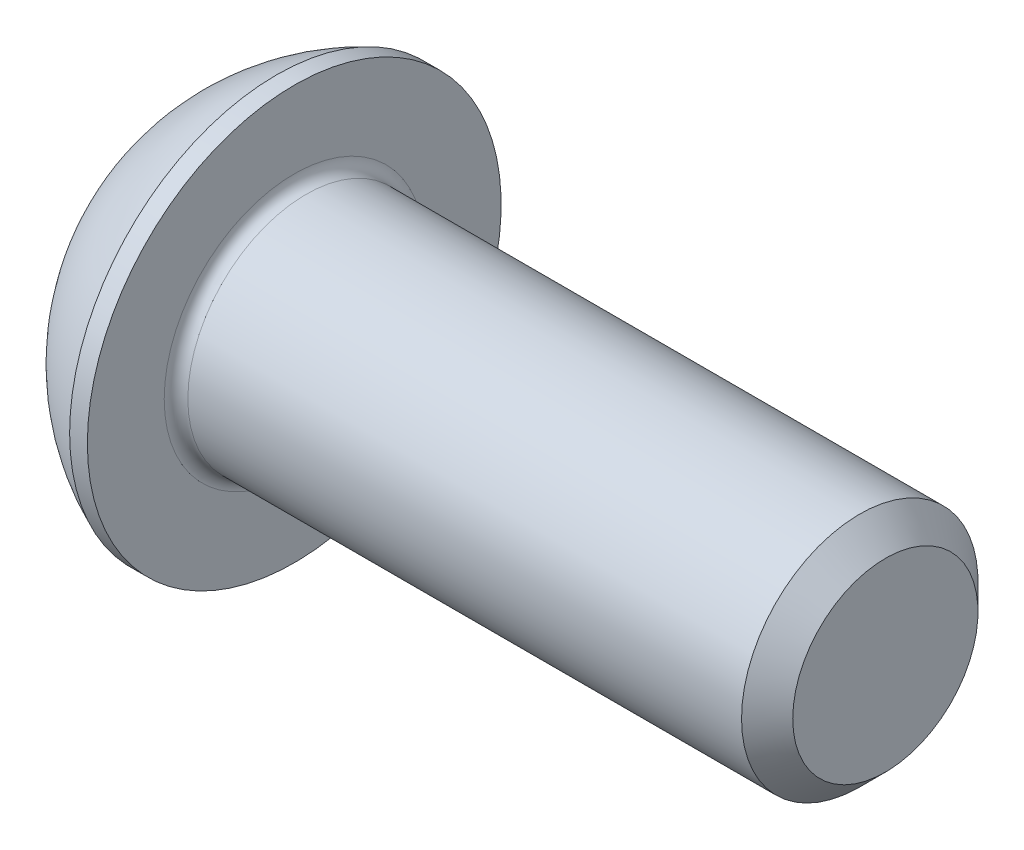
SolidWorks part; units mm, degrees
ref_plane "Plane1" through (0, 0, 0) normal (0, 0, 1) x (1, 0, 0)
ref_plane "Plane2" through (0, 0, 0) normal (0, 1, 0) x (1, 0, 0)
ref_plane "Plane3" through (0, 0, 0) normal (1, 0, 0) x (0, 0, -1)
sketch "BodySke" plane through (0, 0, 0) normal (0, 0, 1) x (1, 0, 0)
  line L0 (6.1, 0) -> (6.1, 0.7835)
  line L1 (5.8835, 1) -> (1.1, 1)
  line L2 (1.1, 1) -> (1.1, 1.75)
  line L3 (1.1, 1.75) -> (0.95, 1.75)
  line L4 (0, 0) -> (101.6, 0) construction
  line L5 (1.1, -1.75) -> (0.95, -1.75) construction
  line L6 (55.6768, -1) -> (1.1, -1) construction
  line L7 (6.1, 0) -> (0, 0)
  line L8 (0, 0.875) -> (0, -0.875) construction
  line L9 (0, 0) -> (0, 0.875)
  line L10 (6.1, 0.7835) -> (5.8835, 1)
  line L11 (6.1, -0.7835) -> (5.8835, -1) construction
  line L12 (1.5, 9.525) -> (1.5, -1) construction
  line L13 (1.1, 9.525) -> (1.1, -1) construction
  arc A1 (0, 0.875) -> (0.95, 1.75) centre (1.6839, 0) cw
  dimension "Diameter" = 2
  dimension "Length" = 5
  dimension "Head_dia" = 3.5
  dimension "D1" = 1.75
  dimension "Head_ht" = 1.1
  dimension "Head_side_ht" = 0.15
  dimension "Minor_dia" = 1.567
  dimension "Body_ch_ang" = 45
  dimension "Advance" = 0.4
  dimension "Thread_nom" = 5
revolve "BaseBody" add sketch "BodySke" angle 360 about L4
cosmetic thread "ThreadCosmetic" [suppressed] parameters "Thread_length"=4.2, "Thread_minor"=1.567
fillet "Fillet1" radius 0.1 1 edges at (1.1, 0, 1)
sketch "Sketch2" plane through (0, 0, 0) normal (0, 0, 1) x (1, 0, 0)
  line L0 (0, 0.715) -> (0.605, 0.715)
  line L1 (0.605, 0.715) -> (1.0178, 0)
  line L3 (1.0178, 0) -> (0, 0)
  line L4 (0, 0) -> (0, 0.715)
  line L5 (0, -0.715) -> (0.605, -0.715) construction
  line L6 (0, 0) -> (47.625, 0) construction
  dimension "D2" = 60
  dimension "PreBroach_depth" = 0.605
  dimension "PreBroach_dia" = 1.43
revolve "PreBroach" cut sketch "Sketch2" angle 360 about L6
sketch "Sketch3" plane through (0, 0, 0) normal (1, 0, 0) x (0, 0, -1)
  line L0 (-0.65, -0.3753) -> (-0.65, 0.3753)
  line L1 (-0.65, 0.3753) -> (0, 0.7506)
  line L2 (0, 0.7506) -> (0.65, 0.3753)
  line L3 (0.65, 0.3753) -> (0.65, -0.3753)
  line L4 (0.65, -0.3753) -> (0, -0.7506)
  line L5 (0, -0.7506) -> (-0.65, -0.3753)
  dimension "Hex_size" = 1.3
  dimension "D3" = 1.3
  dimension "D1" = 0.65
  dimension "D2" = 0.65
extrude "Hex" cut sketch "Sketch3" along normal blind 0.605
sketch "ThdSchSke" plane through (0, 0, 0) normal (0, 0, 1) x (1, 0, 0)
  line L0 (1.9, -0.7835) -> (1.7484, -1)
  line L1 (1.9, -0.7835) -> (2.0516, -1)
  line L2 (2.0516, -1) -> (2.0516, -1.25)
  line L3 (-3.175, 0) -> (5.1513, 0) construction
  line L5 (2.0516, -1.25) -> (1.7484, -1.25)
  line L6 (1.7484, -1.25) -> (1.7484, -1)
  dimension "Diameter" = 2
  dimension "Thread_minor" = 1.567
  dimension "SideAngle" = 55
  dimension "VeeAngle" = 70
  dimension "Overcut" = 2.5
  dimension "Start" = 1.9
revolve "ThreadSchematic" [suppressed] cut sketch "ThdSchSke" angle 360 about L3
pattern_linear "ThdSchPat" [suppressed]
equation "\"D1@BodySke\" = \"Head_dia@BodySke\" * .5"
equation "\"Thread_minor@ThreadCosmetic\" = \"Minor_dia@BodySke\""
equation "\"D1@Sketch3\" = \"Hex_size@Sketch3\" / 2"
equation "\"D2@Sketch3\" = \"D1@Sketch3\""
equation "\"D3@Sketch3\" = \"Hex_size@Sketch3\""
equation "\"Thread_length@ThreadCosmetic\" = ((sgn( (\"Length@BodySke\" - \"Advance@BodySke\" * 2.0) - \"Thread_nom@BodySke\" )-1)*( (\"Length@BodySke\" - \"Advance@BodySke\" * 2.0) - \"Thread_nom@BodySke\" ))/-2+ \"Thread_nom@BodySke\""
equation "\"Thread_minor@ThdSchSke\" = \"Minor_dia@BodySke\""
equation "\"Diameter@ThdSchSke\" = \"Diameter@BodySke\""
equation "\"Overcut@ThdSchSke\" = \"Diameter@BodySke\" * 1.25"
equation "\"Start@ThdSchSke\" = \"Head_ht@BodySke\" + \"Length@BodySke\" - \"Thread_length@ThreadCosmetic\"  '---Non-countersunk---"
equation "\"Num_threads@ThdSchPat\" = int( \"Thread_length@ThreadCosmetic\" / \"Advance@BodySke\" + 0.999 )  + 1"
equation "\"Advance@ThdSchPat\" = \"Thread_length@ThreadCosmetic\" /  (\"Num_threads@ThdSchPat\" - 1) 'relax it"
equation "\"Num_threads@ThdSchPat\" = \"Num_threads@ThdSchPat\" - sgn( \"Num_threads@ThdSchPat\" - 1) '---chamfered tips only---"
